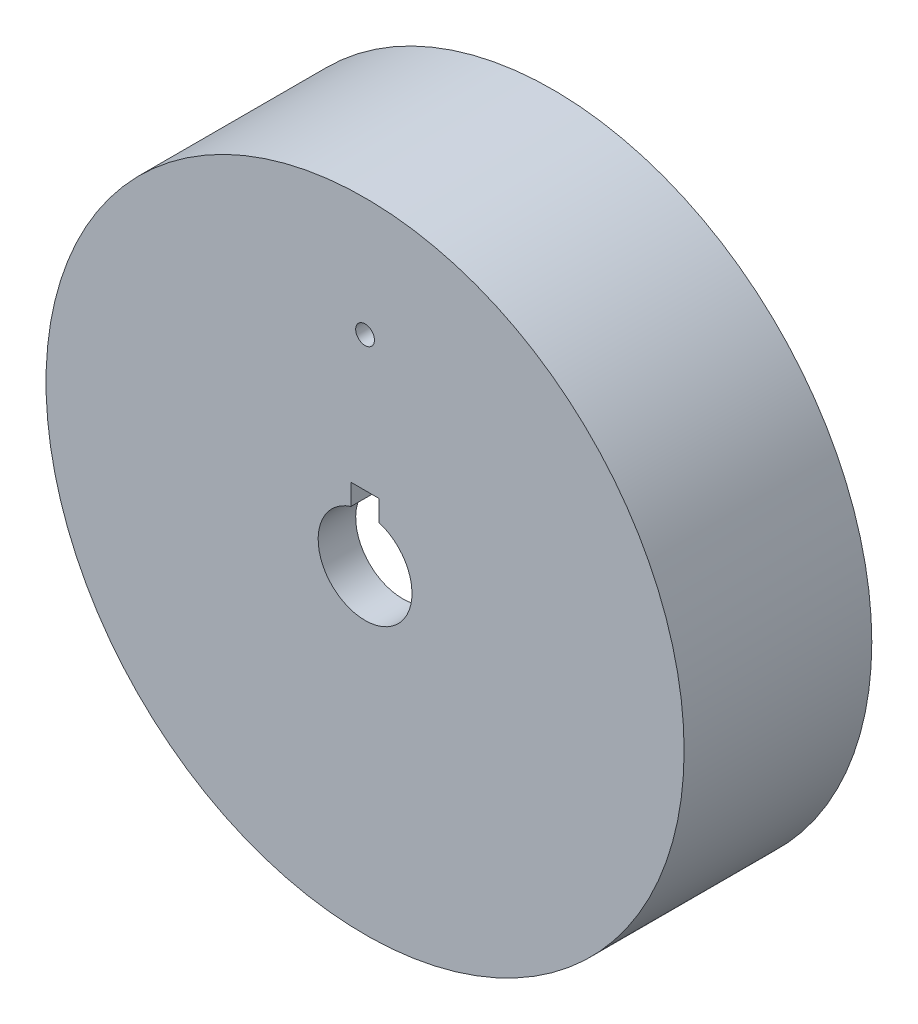
SolidWorks part; units mm, degrees
ref_plane "Alzado" through (0, 0, 0) normal (0, 0, 1) x (1, 0, 0)
ref_plane "Planta" through (0, 0, 0) normal (0, 1, 0) x (1, 0, 0)
ref_plane "Vista lateral" through (0, 0, 0) normal (1, 0, 0) x (0, 0, -1)
sketch "Croquis2" plane through (0, 0, 0) normal (0, 0, 1) x (1, 0, 0)
  line L0 (0, 0) -> (0, 50000) construction
  line L1 (0, 0) -> (-50000, 0) construction
  line L2 (0, 0) -> (35355.3391, 35355.3391) construction
  line L3 (0, 0) -> (-35355.3391, 35355.3391) construction
  circle A0 centre (0, 0) radius 170
  circle A1 centre (0, 0) radius 150
  circle A2 centre (0, 0) radius 67.5
  circle A3 centre (0, 0) radius 25
  dimension "D1" = 340
  dimension "D2" = 300
  dimension "D3" = 135
  dimension "D4" = 50
extrude "Saliente-Extruir1" add sketch "Croquis2" along normal blind 100 contours A0 A1 | A1 A2 | A2 A3
sketch "Croquis3" plane through (0, 0, 0) normal (0, 0, 1) x (1, 0, 0)
  circle A0 centre (0, 0) radius 150
  dimension "D1" = 300
extrude "Cortar-Extruir1" cut sketch "Croquis3" along normal blind 50
sketch "Croquis4" plane through (0, 0, 0) normal (0, 0, 1) x (1, 0, 0)
  circle A0 centre (0, 0) radius 67.5
  dimension "D1" = 135
extrude "Cortar-Extruir3" cut sketch "Croquis4" along normal blind 80
sketch "Croquis5" plane through (0, 0, 0) normal (0, 0, 1) x (1, 0, 0)
  line L1 (-7.5, 0) -> (7.5, 0)
  line L2 (-7.5, 0) -> (-7.5, 35)
  line L3 (-7.5, 35) -> (7.5, 35)
  line L4 (7.5, 0) -> (7.5, 35)
  point P4 (0, 0)
  point P6 (0, 35)
  dimension "D1" = 15
  dimension "D2" = 0
  dimension "D3" = 35
extrude "Cortar-Extruir4" cut sketch "Croquis5" along normal through all
hole_wizard "Avellanado para tornillo con cabeza avellanada de M81" positions "Croquis6" profile "Croquis8" countersink size "M8" standard "JIS" end condition through all
sketch "Croquis6" plane through (0, 0, 50) normal (0, 0, -1) x (-1, 0, 0)
  point P0 (0, 106.8398)
sketch "Croquis8" plane through (0, 106.8398, 50) normal (1, 0, 0) x (0, 1, 0)
  line L0 (0, 0) -> (0, 50)
  line L1 (0, 50) -> (5, 50)
  line L2 (5, 50) -> (5, 3.65)
  line L3 (5, 3.65) -> (8.65, 0)
  line L5 (8.65, 0) -> (0, 0)
  line L6 (-5, 3.65) -> (-8.65, 0) construction
  line L11 (0, -6.35) -> (0, 107.95) construction
  dimension "Diámetro de taladro hasta el siguiente" = 10
  dimension "Profundidad de taladro hasta el siguiente" = 50
  dimension "Diámetro de avellanado cercano" = 17.3
  dimension "Ángulo de avellanado cercano" = 90
